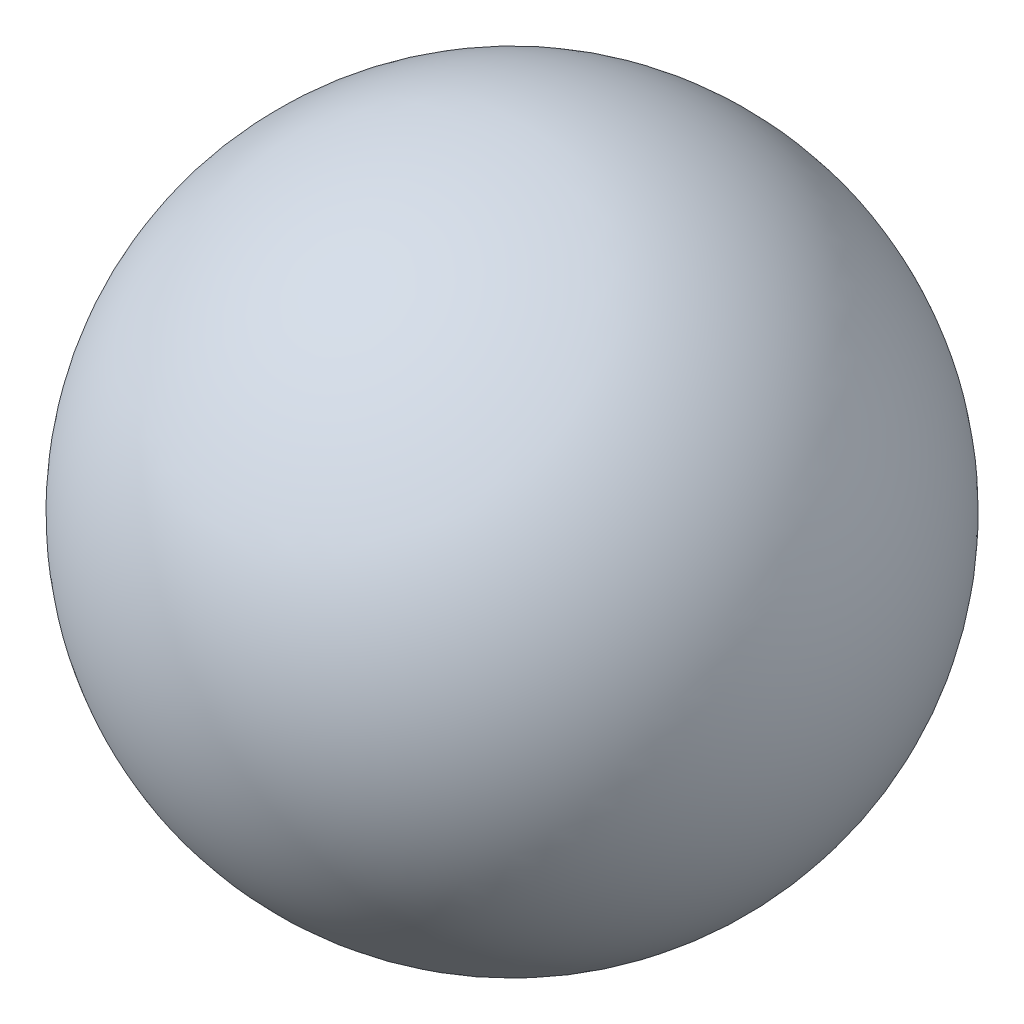
SolidWorks part; units mm, degrees
ref_plane "Front Plane" through (0, 0, 0) normal (0, 0, 1) x (1, 0, 0)
ref_plane "Top Plane" through (0, 0, 0) normal (0, 1, 0) x (1, 0, 0)
ref_plane "Right Plane" through (0, 0, 0) normal (1, 0, 0) x (0, 0, -1)
sketch "Sketch1" plane through (0, 0, 0) normal (0, 1, 0) x (1, 0, 0)
  line L0 (0, -34.29) -> (0, 34.29) construction
  line L1 (0, 34.29) -> (0, -34.29)
  circle A0 centre (0, 0) radius 34.29 construction
  arc A1 (0, 34.29) -> (0, -34.29) centre (0, 0) cw
  dimension "D1" = 68.58
revolve "Revolve4" add sketch "Sketch1" angle 360 about L0
